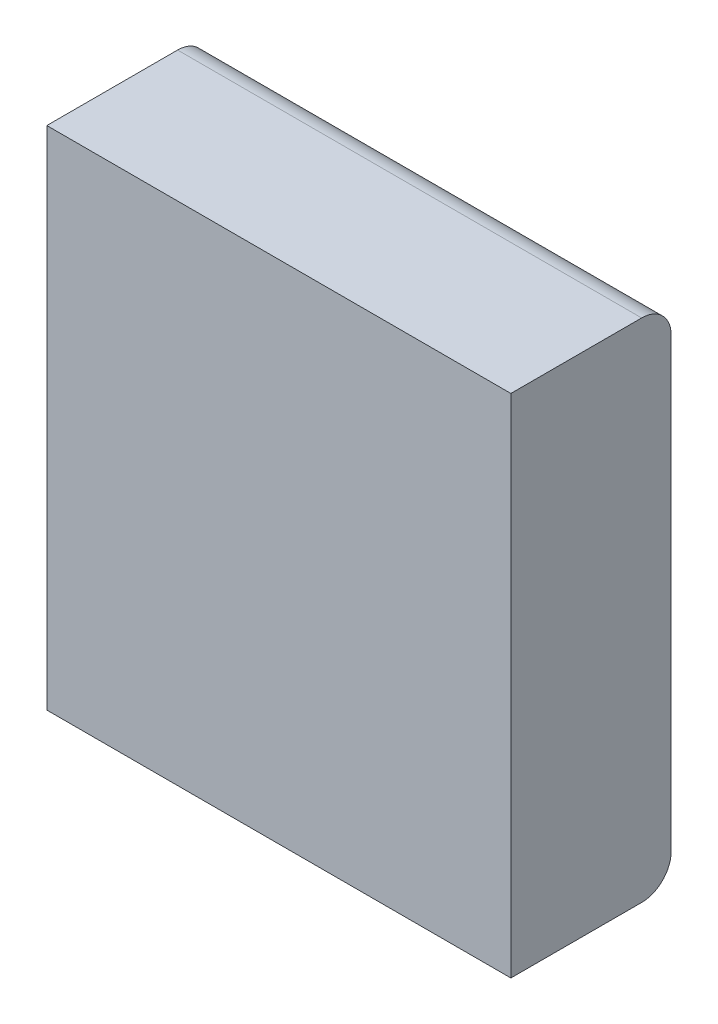
SolidWorks part; units mm, degrees
ref_plane "정면" through (0, 0, 0) normal (0, 0, 1) x (1, 0, 0)
ref_plane "윗면" through (0, 0, 0) normal (0, 1, 0) x (1, 0, 0)
ref_plane "우측면" through (0, 0, 0) normal (1, 0, 0) x (0, 0, -1)
sketch "스케치1" plane through (0, 0, 0) normal (0, 0, 1) x (1, 0, 0)
  line L1 (-64.053, 35.1607) -> (45.947, 35.1607)
  line L2 (-64.053, 35.1607) -> (-64.053, -84.8393)
  line L3 (-64.053, -84.8393) -> (45.947, -84.8393)
  line L4 (45.947, 35.1607) -> (45.947, -84.8393)
  dimension "D1" = 110
  dimension "D2" = 120
extrude "보스-돌출1" add sketch "스케치1" along normal blind 30
sketch "스케치2" plane through (45.947, 0, 0) normal (1, 0, 0) x (0, 0, -1)
  line L1 (0, 35.1607) -> (1, 35.1607)
  line L2 (0, 35.1607) -> (0, -84.8393)
  line L3 (0, -84.8393) -> (1, -84.8393)
  line L4 (8, 28.1607) -> (8, -77.8393)
  arc A0 (1, -84.8393) -> (8, -77.8393) centre (1, -77.8393) ccw
  arc A1 (1, 35.1607) -> (8, 28.1607) centre (1, 28.1607) cw
  point P7 (8, -84.8393)
  dimension "D2" = 7
  dimension "D1" = 8
extrude "보스-돌출2" add sketch "스케치2" against normal blind 110
sketch "스케치3" plane through (0, 0, -8) normal (0, 0, -1) x (-1, 0, 0)
  line L0 (-45.947, -77.8393) -> (-45.947, 28.1607) construction
  line L1 (-35.947, -54.8393) -> (4.053, -54.8393)
  line L2 (-35.947, -54.8393) -> (-35.947, 5.1607)
  line L3 (-35.947, 5.1607) -> (4.053, 5.1607)
  line L4 (4.053, -54.8393) -> (4.053, 5.1607)
  line L5 (64.053, 35.1607) -> (-45.947, 35.1607) construction
  line L6 (64.053, -84.8393) -> (-45.947, -84.8393) construction
  dimension "D1" = 10
  dimension "D2" = 30
  dimension "D3" = 30
  dimension "D4" = 40
extrude "컷-돌출1" cut sketch "스케치3" against normal blind 3
